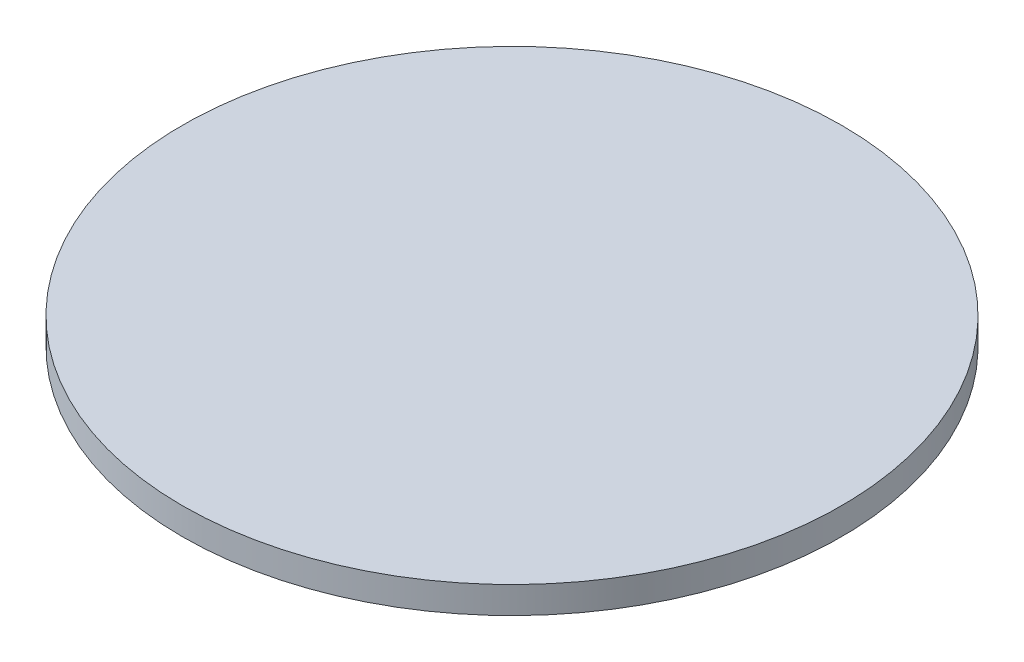
SolidWorks part; units mm, degrees
material "Сосна"
ref_plane "Спереди" through (0, 0, 0) normal (0, 0, 1) x (1, 0, 0)
ref_plane "Сверху" through (0, 0, 0) normal (0, 1, 0) x (1, 0, 0)
ref_plane "Справа" through (0, 0, 0) normal (1, 0, 0) x (0, 0, -1)
sketch "Эскиз1" plane through (0, 0, 0) normal (0, 1, 0) x (1, 0, 0)
  circle A0 centre (0, 0) radius 49
extrude "Бобышка-Вытянуть1" add sketch "Эскиз1" along normal blind 4
